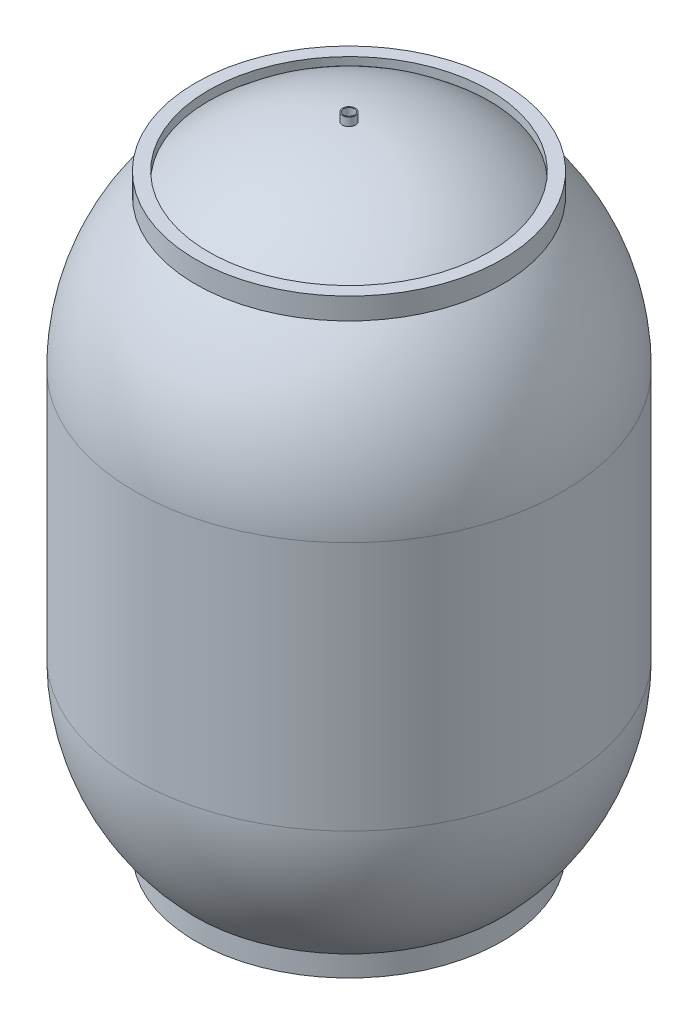
SolidWorks part; units mm, degrees
material "Titanium"
ref_plane "Front Plane" through (0, 0, 0) normal (0, 0, 1) x (1, 0, 0)
ref_plane "Top Plane" through (0, 0, 0) normal (0, 1, 0) x (1, 0, 0)
ref_plane "Right Plane" through (0, 0, 0) normal (1, 0, 0) x (0, 0, -1)
sketch "Sketch1" plane through (0, 0, 0) normal (0, 0, 1) x (1, 0, 0)
  line L1 (0, 0) -> (0, -3141.3) construction
  line L2 (0, -3141.3) -> (0, -3139.07)
  line L4 (0, 2.23) -> (0, 0)
  line L5 (0, -3139.07) -> (0, -2839.07) construction
  line L6 (0, -2839.07) -> (709.9296, -2839.07) construction
  line L7 (709.9296, -2839.07) -> (709.9296, -2939.07)
  line L8 (709.9296, -2939.07) -> (649.9296, -2939.07)
  line L9 (649.9296, -2939.07) -> (649.9296, -2895.8575)
  line L10 (649.9296, -2895.8575) -> (0, -2895.8575) construction
  line L11 (0, -297.77) -> (710.8713, -297.77) construction
  line L12 (710.8713, -297.77) -> (710.8713, -197.77)
  line L13 (710.8713, -197.77) -> (650.8713, -197.77)
  line L14 (650.8713, -197.77) -> (650.8713, -241.0762)
  line L15 (990, -990) -> (990, -2149.07)
  line L16 (992.23, -990) -> (992.23, -2149.07)
  arc A0 (990, -990) -> (0, 0) centre (0, -990) ccw
  arc A1 (992.23, -2149.07) -> (0, -3141.3) centre (0, -2149.07) cw
  arc A2 (0, 2.23) -> (992.23, -990) centre (0, -990) cw
  arc A3 (990, -2149.07) -> (0, -3139.07) centre (0, -2149.07) cw
  dimension "D3" = 990
  dimension "D4" = 992.23
  dimension "D5" = 992.23
  dimension "D6" = 990
  dimension "D2" = 3141.3
  dimension "D7" = 100
  dimension "D8" = 60
  dimension "D9" = 300
  dimension "D10" = 300
  dimension "D11" = 100
  dimension "D12" = 60
  dimension "D14" = 992.23
revolve "Revolve1" add sketch "Sketch1" angle 360 about L1
sketch "Sketch2" plane through (0, 0, 0) normal (0, 1, 0) x (1, 0, 0)
  circle A0 centre (0, 0) radius 30
  dimension "D1" = 60
extrude "Cut-Extrude1" cut sketch "Sketch2" against normal through all and the other way through all
sketch "Sketch3" plane through (0, 0, 0) normal (0, 1, 0) x (1, 0, 0)
  circle A0 centre (0, 0) radius 30
  circle A1 centre (0, 0) radius 25
  dimension "D1" = 50
  dimension "D2" = 60
extrude "Boss-Extrude2" add sketch "Sketch3" along normal blind 40
pattern_linear "LPattern1" count 2 spacing 3179.07 along (0, -1, 0) of "Boss-Extrude2"
